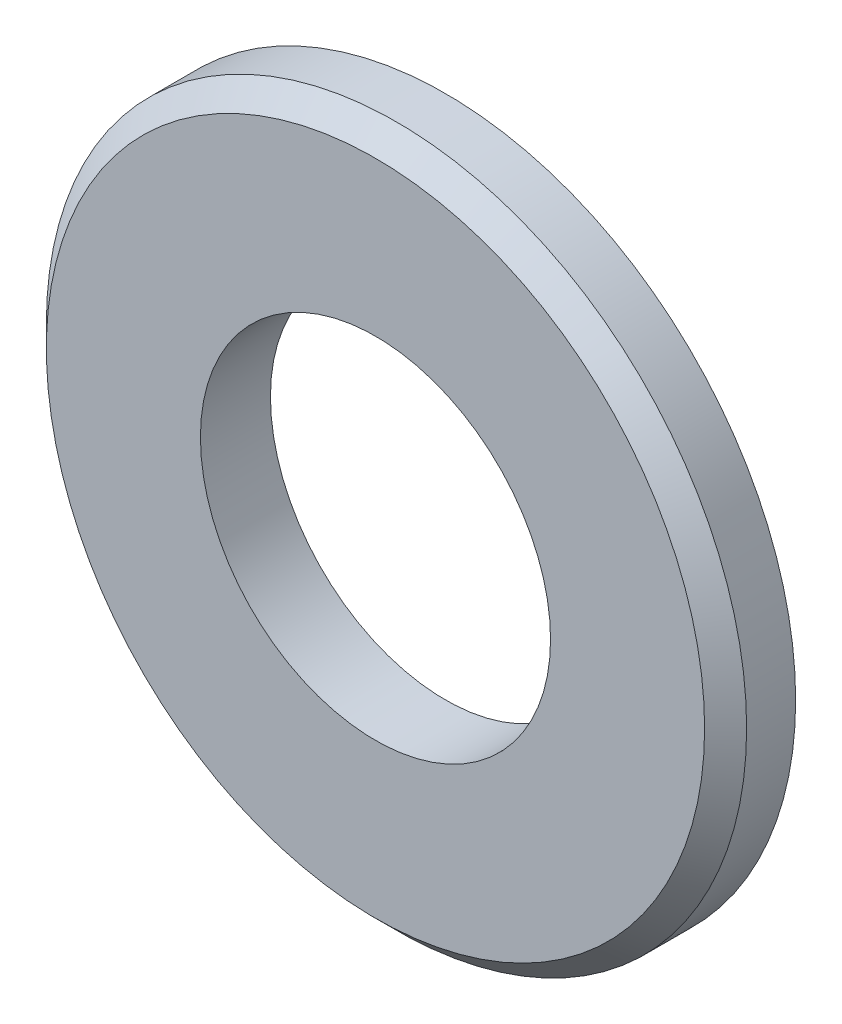
SolidWorks part; units mm, degrees
ref_plane "Alzado" through (0, 0, 0) normal (0, 0, 1) x (1, 0, 0)
ref_plane "Planta" through (0, 0, 0) normal (0, 1, 0) x (1, 0, 0)
ref_plane "Vista lateral" through (0, 0, 0) normal (1, 0, 0) x (0, 0, -1)
sketch "Croquis1" plane through (0, 0, 0) normal (0, 0, 1) x (1, 0, 0)
  circle A0 centre (0, 0) radius 2.5
  circle A1 centre (0, 0) radius 5
  dimension "D1" = 5
  dimension "D2" = 10
extrude "Saliente-Extruir1" add sketch "Croquis1" against normal blind 1
chamfer "Chaflán1" distance 0.3 angle 45 1 edges at (5, 0, 0)
